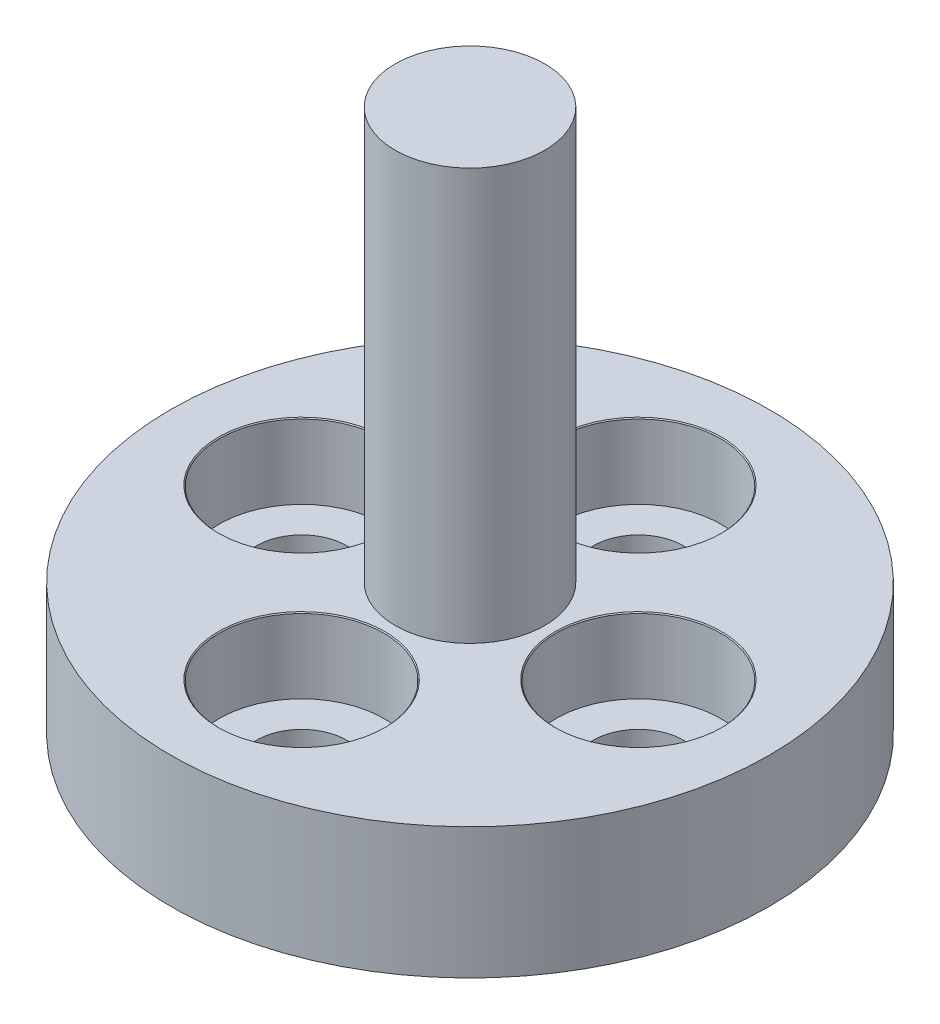
SolidWorks part; units mm, degrees
ref_plane "Front Plane" through (0, 0, 0) normal (0, 0, 1) x (1, 0, 0)
ref_plane "Top Plane" through (0, 0, 0) normal (0, 1, 0) x (1, 0, 0)
ref_plane "Right Plane" through (0, 0, 0) normal (1, 0, 0) x (0, 0, -1)
sketch "Sketch1" plane through (0, 0, 0) normal (0, 0, 1) x (1, 0, 0)
  line L0 (0, 0) -> (8, 0)
  line L1 (8, 0) -> (8, 3.5)
  line L2 (8, 3.5) -> (2, 3.5)
  line L3 (2, 3.5) -> (2, 14.5)
  line L4 (2, 14.5) -> (0, 14.5)
  line L5 (0, 14.5) -> (0, 0)
  dimension "D1" = 8
  dimension "D2" = 2
  dimension "D3" = 11
  dimension "D4" = 14.5
revolve "Revolve1" add sketch "Sketch1" angle 360 about L5
sketch "Sketch2" plane through (0, 3.5, 0) normal (0, 1, 0) x (1, 0, 0)
  circle A0 centre (0, 0) radius 4.5
hole_wizard "CBORE for M2 SHCS1" positions "Sketch4" profile "Sketch5" counterbore size "M2" standard "ANSI Metric" end condition through all
sketch "Sketch4" plane through (0, 3.5, 0) normal (0, 1, 0) x (1, 0, 0)
  circle A0 centre (0, 0) radius 4.5 construction
  point P0 (-4.5, 0)
  point P4 (0, 4.5)
  point P6 (4.5, 0)
  point P8 (0, -4.5)
sketch "Sketch5" plane through (-4.5, 3.5, 0) normal (1, 0, 0) x (0, 0, 1)
  line L0 (0, 0) -> (0, 3.5)
  line L1 (0, 3.5) -> (1.2, 3.5)
  line L3 (1.2, 3.5) -> (1.2, 2)
  line L4 (2.2, 2) -> (1.2, 2)
  line L5 (2.2, 2) -> (2.2, 0.025)
  line L6 (2.2, 0.025) -> (2.225, 0)
  line L7 (2.225, 0) -> (0, 0)
  line L8 (-2.2, 0.025) -> (-2.225, 0) construction
  line L11 (0, -6.35) -> (0, 107.95) construction
  dimension "Thru Hole Dia." = 2.4
  dimension "Thru Hole Depth" = 3.5
  dimension "C'Bore Dia." = 4.4
  dimension "C'Bore Depth" = 2
  dimension "Near C'Sink Dia." = 4.45
  dimension "Near C'Sink Angle" = 90
